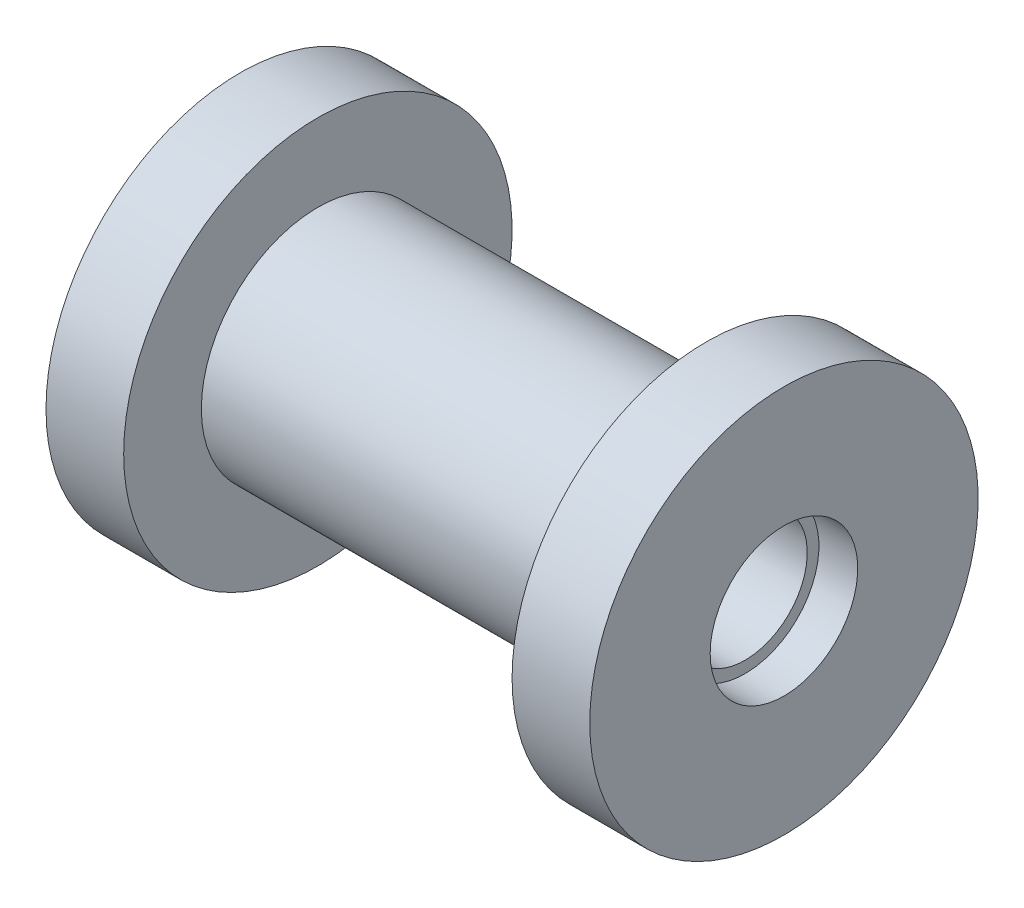
SolidWorks part; units mm, degrees
ref_plane "前视基准面" through (0, 0, 0) normal (0, 0, 1) x (1, 0, 0)
ref_plane "上视基准面" through (0, 0, 0) normal (0, 1, 0) x (1, 0, 0)
ref_plane "右视基准面" through (0, 0, 0) normal (1, 0, 0) x (0, 0, -1)
sketch "草图1" plane through (0, 0, 0) normal (0, 0, 1) x (1, 0, 0)
  line L0 (-69.3944, 0) -> (86.8012, 0) construction
  line L1 (0, 72.5293) -> (0, -41.2337) construction
  line L2 (0, 9.5) -> (0, 25)
  line L3 (0, 25) -> (10, 25)
  line L4 (10, 25) -> (10, 15)
  line L5 (10, 15) -> (60, 15)
  line L6 (60, 15) -> (60, 25)
  line L7 (60, 25) -> (70, 25)
  line L8 (70, 25) -> (70, 9.5)
  line L9 (0, 9.5) -> (5, 9.5)
  line L10 (5, 9.5) -> (5, 8)
  line L11 (70, 9.5) -> (65, 9.5)
  line L12 (65, 9.5) -> (65, 8)
  line L13 (5, 8) -> (65, 8)
  point P2 (0, 9.5)
  point P5 (0, 25)
revolve "旋转2" add sketch "草图1" angle 360 about L0
